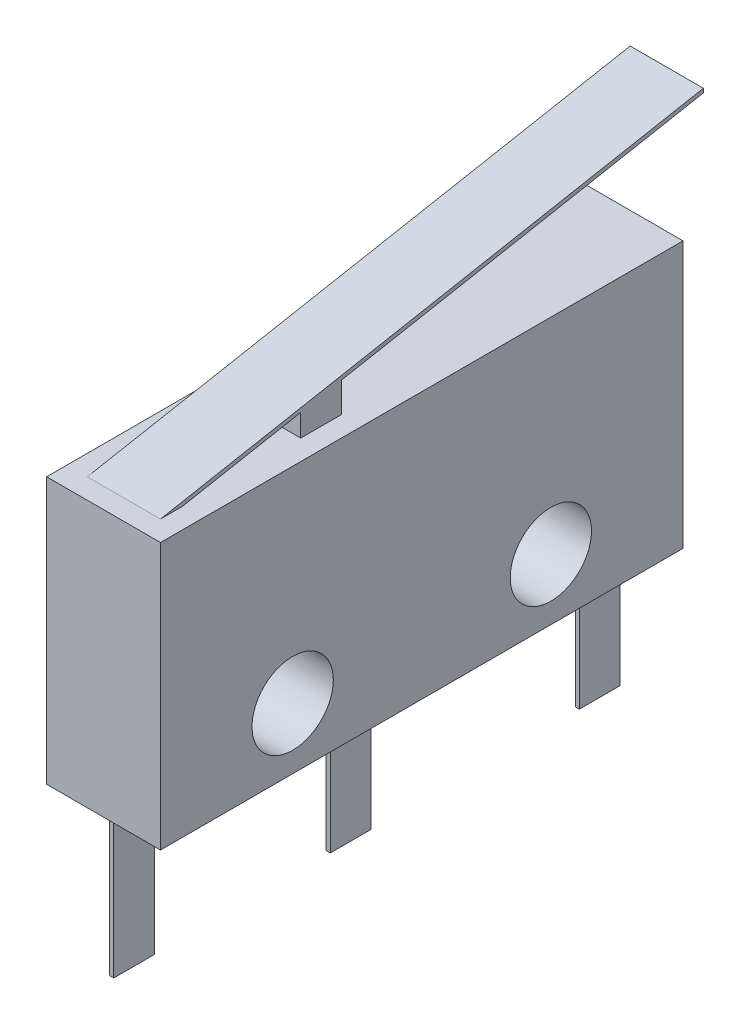
SolidWorks part; units mm, degrees
ref_plane "Front Plane" through (0, 0, 0) normal (0, 0, 1) x (1, 0, 0)
ref_plane "Top Plane" through (0, 0, 0) normal (0, 1, 0) x (1, 0, 0)
ref_plane "Right Plane" through (0, 0, 0) normal (1, 0, 0) x (0, 0, -1)
sketch "BodySketch1" plane through (0, 0, 0) normal (1, 0, 0) x (0, 0, -1)
  line L1 (0, 0) -> (12.85, 0)
  line L2 (0, 0) -> (0, 6.55)
  line L3 (0, 6.55) -> (12.85, 6.55)
  line L4 (12.85, 0) -> (12.85, 6.55)
  circle A0 centre (3.25, 1.5) radius 1
  circle A1 centre (9.6, 1.5) radius 1
  dimension "D6" = 2
  dimension "D1" = 12.85
  dimension "D2" = 6.55
  dimension "D3" = 1.5
  dimension "D4" = 3.25
  dimension "D5" = 6.35
  dimension "D7" = 3.25
extrude "BodyBoss-Extrude1" add sketch "BodySketch1" along normal blind 2.8
sketch "Sketch2" plane through (0, 6.55, 0) normal (0, 1, 0) x (1, 0, 0)
  line L0 (2.8, 12.85) -> (2.8, 0) construction
  line L1 (0.5, 0.5) -> (2.3, 0.5)
  line L2 (0.5, 0.5) -> (0.5, 13.85)
  line L3 (0.5, 13.85) -> (2.3, 13.85)
  line L4 (2.3, 0.5) -> (2.3, 13.85)
  line L5 (0, 12.85) -> (0, 0) construction
  line L6 (2.8, 0) -> (0, 0) construction
  line L7 (2.8, 12.85) -> (0, 12.85) construction
  dimension "D1" = 0.5
  dimension "D2" = 0.5
  dimension "D3" = 0.5
  dimension "D4" = 1
extrude "LeverBoss-Extrude2" add sketch "Sketch2" along normal blind 2.5
sketch "Sketch3" plane through (2.3, 0, 0) normal (1, 0, 0) x (0, 0, -1)
  line L0 (0.5, 6.55) -> (13.85, 9.05)
  line L1 (13.85, 9.05) -> (13.85, 6.55) construction
  line L2 (0.5, 9.05) -> (13.85, 9.05) construction
  line L3 (13.85, 9.05) -> (0.5, 9.05)
  line L4 (0.5, 9.05) -> (0.5, 6.55)
  line L5 (13.85, 8.95) -> (13.85, 6.55)
  line L6 (13.85, 6.55) -> (1.034, 6.55)
  line L7 (12.85, 6.55) -> (0, 6.55) construction
  line L8 (1.034, 6.55) -> (13.85, 8.95)
extrude "LeverCut-Extrude1" cut sketch "Sketch3" against normal through all
sketch "Sketch4" plane through (0, 6.55, 0) normal (0, 1, 0) x (1, 0, 0)
  line L0 (0.5, 0.5) -> (0.5, 13.85) construction
  line L1 (0.5, 4.9489) -> (2.3, 4.9489)
  line L2 (0.5, 4.9489) -> (0.5, 3.9489)
  line L3 (0.5, 3.9489) -> (2.3, 3.9489)
  line L4 (2.3, 4.9489) -> (2.3, 3.9489)
  line L5 (2.3, 0.5) -> (2.3, 13.85) construction
  dimension "D1" = 1
extrude "ButtonBoss-Extrude3" add sketch "Sketch4" along normal up to next
sketch "Sketch5" plane through (0, 0, 0) normal (0, -1, 0) x (1, 0, 0)
  line L0 (2.8, 0) -> (2.8, -12.85) construction
  line L1 (1.35, -0.2) -> (1.45, -0.2)
  line L2 (1.35, -0.2) -> (1.35, -1.2)
  line L3 (1.35, -1.2) -> (1.45, -1.2)
  line L4 (1.45, -0.2) -> (1.45, -1.2)
  line L5 (1.35, -5.525) -> (1.45, -5.525)
  line L6 (1.35, -5.525) -> (1.35, -6.525)
  line L7 (1.35, -6.525) -> (1.45, -6.525)
  line L8 (1.45, -5.525) -> (1.45, -6.525)
  line L9 (1.35, -11.65) -> (1.45, -11.65)
  line L10 (1.35, -11.65) -> (1.35, -12.65)
  line L11 (1.35, -12.65) -> (1.45, -12.65)
  line L12 (1.45, -11.65) -> (1.45, -12.65)
  line L13 (2.8, 0) -> (0, 0) construction
  line L14 (2.8, -12.85) -> (0, -12.85) construction
  line L15 (0, 0) -> (0, -12.85) construction
  dimension "D2" = 1.35
  dimension "D4" = 0.2
  dimension "D5" = 0.2
  dimension "D6" = 6.325
extrude "TereminalBoss-Extrude4" add sketch "Sketch5" along normal blind 3.5
equation "\"MicroSwitchLength\"= 12.85mm"
equation "\"D1@BodySketch1\" = \"MicroSwitchLength\""
equation "\"MicroSwitchHeight\"= 6.55mm"
equation "\"D2@BodySketch1\" = \"MicroSwitchHeight\""
equation "\"MicroSwitchMountHoleOffsetFromBottom\"= 1.5mm"
equation "\"MicroSwitchMountHoleOffsetFromSide\"= 3.25mm"
equation "\"D4@BodySketch1\" = \"MicroSwitchMountHoleOffsetFromSide\""
equation "\"MicroSwitchMountHoleDiameter\"= 2mm"
equation "\"D6@BodySketch1\" = \"MicroSwitchMountHoleDiameter\""
equation "\"MicroSwitchDepth\"= 2.8mm"
equation "\"D1@BodyBoss-Extrude1\" = \"MicroSwitchDepth\""
equation "\"MicroSwitchLeverHeight\"= 2.5mm"
equation "\"D1@LeverBoss-Extrude2\" = \"MicroSwitchLeverHeight\""
equation "\"D2@Sketch5\"=(\"MicroSwitchDepth\"-.1)/2"
equation "\"D6@Sketch5\"=(\"MicroSwitchLength\" -.2)/2"
equation "\"MicroSwitchTerminalHeight\"= 3.5mm"
equation "\"D1@TereminalBoss-Extrude4\" = \"MicroSwitchTerminalHeight\""
equation "\"MicroSwitchTerminalWidth\"= .2mm"
equation "\"MicroSwitchTerminalDepth\"= .1mm"
equation "\"D1@Sketch5\"=\"MicroSwitchTerminalDepth\""
equation "\"MicroSwitchLeverDepth\"= .1mm"
equation "\"D1@Sketch3\"=\"MicroSwitchLeverDepth\""
equation "\"D3@BodySketch1\"=\"MicroSwitchMountHoleOffsetFromBottom\""
equation "\"D5@Sketch5\"=\"MicroSwitchTerminalWidth\""
equation "\"MicroSwitchDistanceBetweenMountingHoles\" = 6.35mm"
equation "\"D5@BodySketch1\"=\"MicroSwitchDistanceBetweenMountingHoles\""
